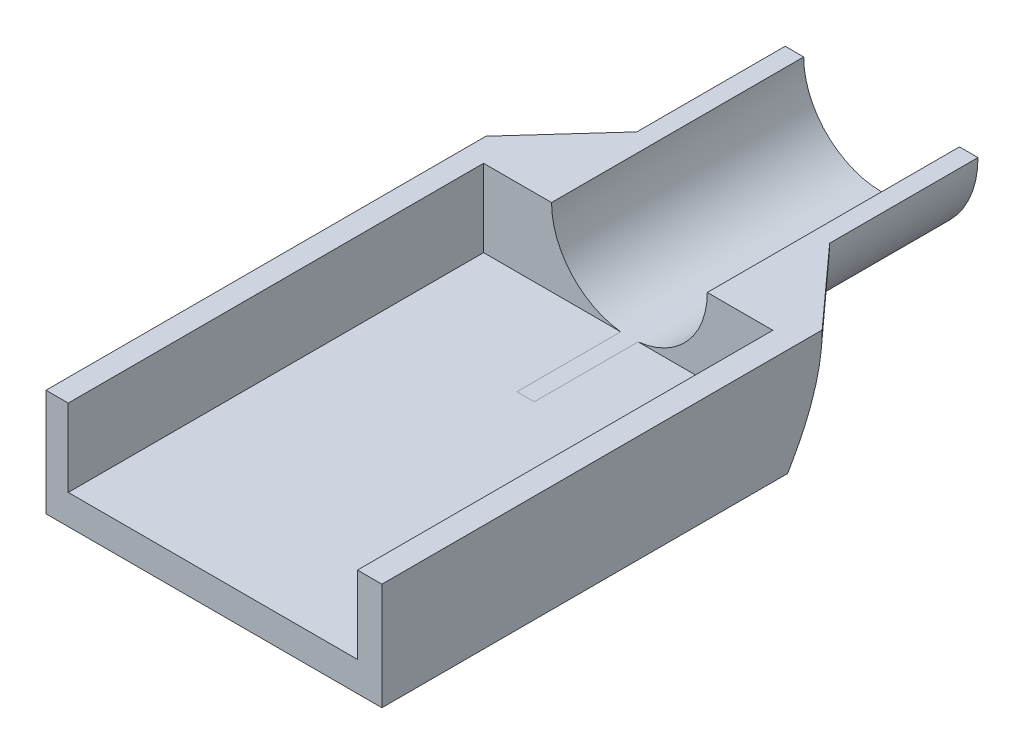
SolidWorks part; units mm, degrees
ref_plane "Front Plane" through (0, 0, 0) normal (0, 0, 1) x (1, 0, 0)
ref_plane "Top Plane" through (0, 0, 0) normal (0, 1, 0) x (1, 0, 0)
ref_plane "Right Plane" through (0, 0, 0) normal (1, 0, 0) x (0, 0, -1)
sketch "Sketch1" plane through (0, 0, 0) normal (0, 1, 0) x (1, 0, 0)
  line L0 (-14.0844, 16.5176) -> (-1.0844, 16.5176)
  line L1 (-1.0844, 16.5176) -> (-1.0844, -3.4824)
  line L2 (17.9156, -24.4824) -> (17.9156, -73.4824)
  line L3 (17.9156, -73.4824) -> (-14.0844, -73.4824)
  line L4 (-14.0844, -73.4824) -> (-14.0844, 16.5176)
  line L5 (-1.0844, -3.4824) -> (17.9156, -24.4824)
  dimension "D4" = 32
  dimension "D1" = 49
  dimension "D2" = 20
  dimension "D3" = 90
  dimension "D5" = 13
revolve "Revolve1" add sketch "Sketch1" angle 360 about L4
sketch "Sketch7" plane through (0, 0, 73.4824) normal (0, 0, 1) x (1, 0, 0)
  line L0 (-14.0844, 32) -> (-14.0844, -32)
  line L1 (-46.0844, 0) -> (17.9156, 0)
  line L2 (-14.0844, 0) -> (8.543, 22.6274)
  line L4 (8.543, 22.6274) -> (-36.7479, 22.6274)
  line L5 (8.543, 22.6274) -> (8.543, -22.5913)
  line L6 (8.543, -22.5913) -> (-36.7479, -22.5913)
  line L7 (-36.7479, 22.6274) -> (-36.7479, -22.5913)
  circle A0 centre (-14.0844, 0) radius 32 construction
  circle M1 centre (-14.0844, 0) radius 32
extrude "Cut-Extrude6" cut sketch "Sketch7" against normal blind 75 contours L4 L0 M1 | L7 L1 M1 | L7 L1 M1 | L0 L6 M1 | L5 L1 M1 | L5 L6 L0 L1 M1 | L4 L0 M1
sketch "Sketch10" plane through (0, 0, -16.5176) normal (0, 0, -1) x (-1, 0, 0)
  line L0 (14.0844, 13) -> (14.0844, -13)
  line L1 (27.0844, 0) -> (1.0844, 0)
  circle A0 centre (14.0844, 0) radius 13 construction
  circle A1 centre (14.0844, 0) radius 13 construction
  circle A2 centre (14.0844, 0) radius 10.5
  dimension "D1" = 21
extrude "Cut-Extrude7" cut sketch "Sketch10" against normal blind 48 contours L0 A2 L1 | L1 A2 L0 | L0 A2 L1 | L1 A2 L0
sketch "Sketch11" plane through (0, 0, 73.4824) normal (0, 0, 1) x (1, 0, 0)
  line L0 (-36.7479, 22.5913) -> (-36.7479, -22.5913) construction
  line L1 (-33.7479, 11.5657) -> (5.2521, 11.5657)
  line L2 (-33.7479, 11.5657) -> (-33.7479, -10.4343)
  line L3 (-33.7479, -10.4343) -> (5.2521, -10.4343)
  line L4 (5.2521, 11.5657) -> (5.2521, -10.4343)
  line L5 (8.543, 22.6274) -> (8.543, -22.5913) construction
  dimension "D1" = 39
  dimension "D2" = 22
  dimension "D3" = 3
  dimension "D4" = 3.2909
extrude "Cut-Extrude8" cut sketch "Sketch11" against normal blind 56
sketch "Sketch14" plane through (0, 0, 73.4824) normal (0, 0, 1) x (1, 0, 0)
  line L0 (5.2521, 11.5657) -> (-33.7479, 11.5657) construction
  line L1 (-39.5645, 24.2249) -> (11.2565, 24.2249)
  line L2 (-39.5645, 24.2249) -> (-39.5645, 15.5657)
  line L3 (-39.5645, 15.5657) -> (11.2565, 15.5657)
  line L4 (11.2565, 24.2249) -> (11.2565, 15.5657)
  line L5 (-33.7479, -10.4343) -> (5.2521, -10.4343) construction
  line L6 (12.1843, -23.5058) -> (-42.9663, -23.5058)
  line L7 (12.1843, -23.5058) -> (12.1843, -14.4343)
  line L8 (12.1843, -14.4343) -> (-42.9663, -14.4343)
  line L9 (-42.9663, -23.5058) -> (-42.9663, -14.4343)
  dimension "D1" = 4
  dimension "D2" = 4
extrude "Cut-Extrude11" cut sketch "Sketch14" against normal blind 90
sketch "Sketch15" plane through (0, 0, -16.5176) normal (0, 0, -1) x (-1, 0, 0)
  line L2 (39.1196, 0) -> (-13.4724, 0)
  line L3 (39.1196, 0) -> (39.1196, 17.9498)
  line L4 (39.1196, 17.9498) -> (-13.4724, 17.9498)
  line L5 (-13.4724, 0) -> (-13.4724, 17.9498)
extrude "Cut-Extrude12" cut sketch "Sketch15" against normal blind 100
